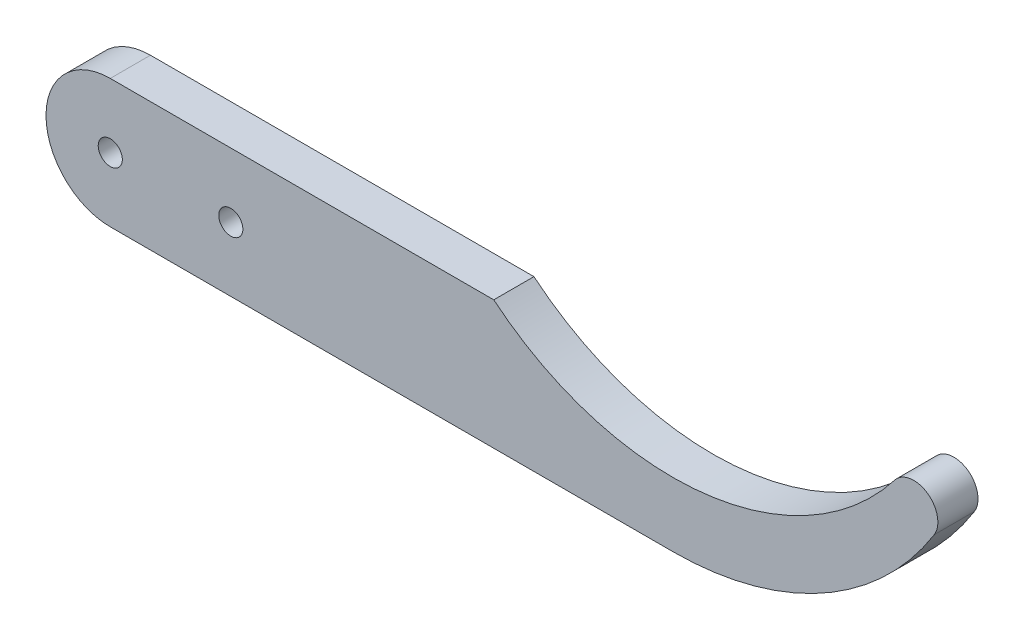
SolidWorks part; units mm, degrees
ref_plane "Plan de face" through (0, 0, 0) normal (0, 0, 1) x (1, 0, 0)
ref_plane "Plan de dessus" through (0, 0, 0) normal (0, 1, 0) x (1, 0, 0)
ref_plane "Plan de droite" through (0, 0, 0) normal (1, 0, 0) x (0, 0, -1)
sketch "Esquisse1" plane through (0, 0, 0) normal (0, 0, 1) x (1, 0, 0)
  line L0 (0, 0) -> (80, 0) construction
  line L1 (20, 0) -> (20, 23.8674) construction
  line L2 (0, 0) -> (0, 35) construction
  line L3 (0, 35) -> (55, 35) construction
  line L4 (0, 8) -> (20, 8)
  line L5 (82.6316, 13.5175) -> (85, 11.6762) construction
  line L6 (20, 8) -> (32.7289, 8)
  line L7 (0, -8) -> (55, -8)
  line L8 (55, 35) -> (55, -8) construction
  line L9 (0, 8) -> (-15, 8)
  line L10 (0, 0) -> (-15, 0) construction
  line L11 (0, -8) -> (-15, -8)
  circle A0 centre (0, 0) radius 1.5
  arc A1 (0, 8) -> (0, -8) centre (0, 0) ccw construction
  circle A2 centre (55, 35) radius 35 construction
  arc A3 (32.7289, 8) -> (82.6316, 13.5175) centre (55, 35) ccw
  arc A4 (82.6316, 13.5175) -> (87.5479, 10.0925) centre (85, 11.6762) cw
  arc A5 (55, -8) -> (87.5479, 10.0925) centre (55, 30.3227) ccw
  circle A6 centre (15, 0) radius 1.5 construction
  arc A7 (-15, 8) -> (-15, -8) centre (-15, 0) ccw
  circle A8 centre (-15, 0) radius 1.5
  dimension "D3" = 3
  dimension "D4" = 35
  dimension "D6" = 70
  dimension "D7" = 3
  dimension "D8" = 8
  dimension "D9" = 30
  dimension "D10" = 15
  dimension "D11" = 8
  dimension "D1" = 20
  dimension "D2" = 80
  dimension "D5" = 55
  dimension "D12" = 15
extrude "Boss.-Extru.1" add sketch "Esquisse1" along normal blind 5
